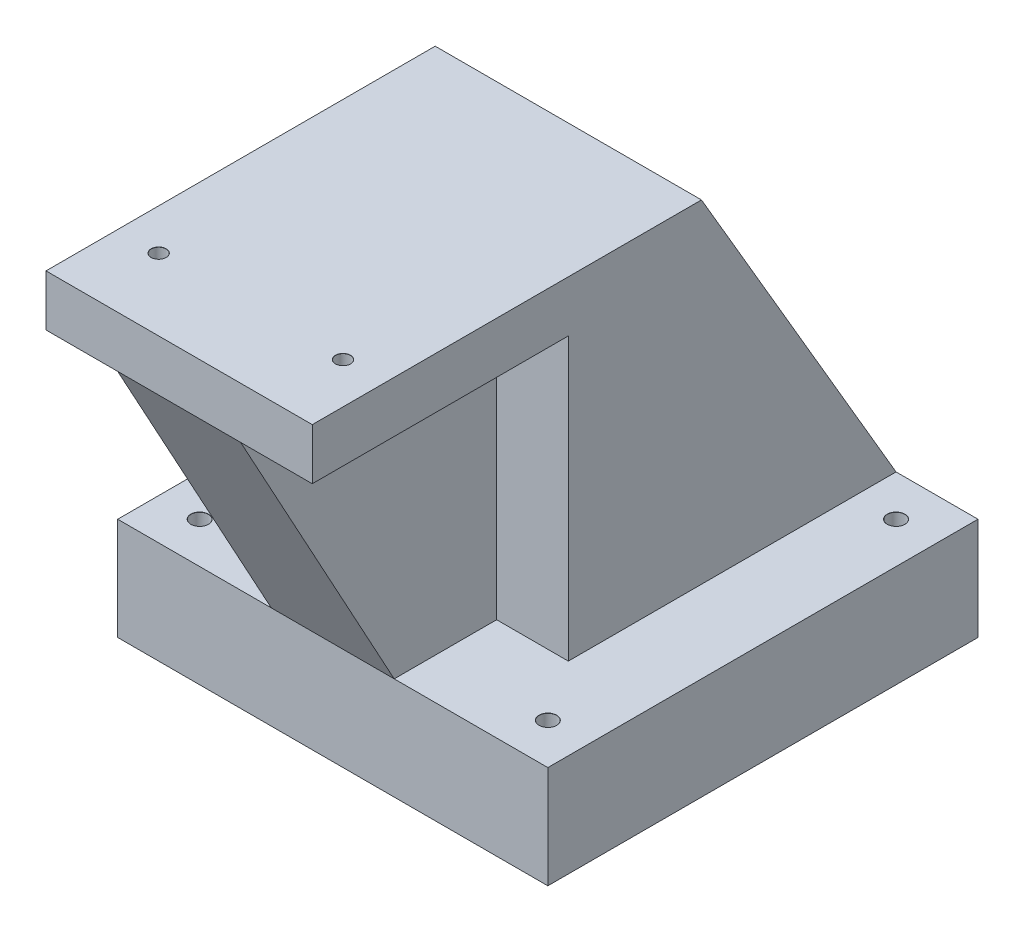
SolidWorks part; units mm, degrees
ref_plane "Front Plane" through (0, 0, 0) normal (0, 0, 1) x (1, 0, 0)
ref_plane "Top Plane" through (0, 0, 0) normal (0, 1, 0) x (1, 0, 0)
ref_plane "Right Plane" through (0, 0, 0) normal (1, 0, 0) x (0, 0, -1)
sketch "Sketch1" plane through (0, 0, 0) normal (0, 1, 0) x (1, 0, 0)
  line L1 (-42, 42) -> (42, 42)
  line L2 (-42, 42) -> (-42, -42)
  line L3 (-42, -42) -> (42, -42)
  line L4 (42, 42) -> (42, -42)
  line L5 (-42, 42) -> (42, -42) construction
  line L6 (-42, -42) -> (42, 42) construction
  point P0 (0, 0)
  dimension "D1" = 84
  dimension "D2" = 84
extrude "Boss-Extrude1" add sketch "Sketch1" along normal blind 20
sketch "Sketch2" plane through (0, 20, 0) normal (0, 1, 0) x (1, 0, 0)
  line L0 (-42, 42) -> (-34, 42) construction
  line L1 (42, 42) -> (-42, 42) construction
  line L2 (-34, 42) -> (-34, 34) construction
  line L3 (42, 34) -> (34, 34) construction
  line L4 (34, -42) -> (34, -34) construction
  line L5 (-42, -34) -> (-34, -34) construction
  point P15 (0, 0)
  dimension "D1" = 8
  dimension "D2" = 8
  dimension "D3" = 4
hole_wizard "M3 Clearance Hole1" positions "Sketch3" profile "Sketch4" hole size "M3" standard "ISO" end condition through all
sketch "Sketch3" plane through (0, 20, 0) normal (0, 1, 0) x (1, 0, 0)
  point P0 (-34, 34)
  point P3 (34, 34)
  point P6 (34, -34)
  point P9 (-34, -34)
sketch "Sketch4" plane through (-34, 20, -34) normal (1, 0, 0) x (0, 0, 1)
  line L0 (0, 0) -> (0, 20)
  line L1 (0, 20) -> (1.7, 20)
  line L2 (1.7, 20) -> (1.7, 0.025)
  line L3 (1.7, 0.025) -> (1.725, 0)
  line L5 (1.725, 0) -> (0, 0)
  line L6 (-1.7, 0.025) -> (-1.725, 0) construction
  line L11 (0, -6.35) -> (0, 107.95) construction
  dimension "Thru Hole Dia." = 3.4
  dimension "Thru Hole Depth" = 20
  dimension "Near C'Sink Dia." = 3.45
  dimension "Near C'Sink Angle" = 90
sketch "Sketch5" plane through (0, 20, 0) normal (0, 1, 0) x (1, 0, 0)
  line L0 (42, -42) -> (42, 42) construction
  line L1 (-42, 4) -> (-26, 4)
  line L2 (-42, 4) -> (-42, -72)
  line L3 (-42, -72) -> (42, -72)
  line L4 (42, 4) -> (42, -72)
  line L5 (-42, 4) -> (42, -72) construction
  line L6 (-42, -72) -> (42, 4) construction
  line L8 (42, 42) -> (-42, 42) construction
  line L9 (-42, 42) -> (-42, -42) construction
  line L11 (-26, 4) -> (-26, 42)
  line L12 (-26, 42) -> (26, 42)
  line L13 (26, 4) -> (26, 42)
  line L14 (26, 4) -> (42, 4)
  line L16 (-42, -42) -> (42, -42) construction
  point P0 (0, 0)
  dimension "D1" = 38
  dimension "D2" = 16
  dimension "D3" = 16
  dimension "D4" = 30
extrude "Boss-Extrude2" add sketch "Sketch5" along normal blind 65
sketch "Sketch7" plane through (0, 85, 0) normal (0, 1, 0) x (1, 0, 0)
  line L0 (0, 42) -> (0, -42) construction
  line L5 (-42, -42) -> (42, -42) construction
  line L6 (42, 4) -> (42, 42) construction
  line L8 (-42, -42) -> (42, -42)
  line L9 (-42, -42) -> (-42, 3)
  line L10 (-42, 3) -> (42, 3)
  line L11 (42, -42) -> (42, 3)
  line L12 (-42, -42) -> (42, 3) construction
  line L13 (-42, 3) -> (42, -42) construction
  line L23 (-37.8179, 3) -> (37.8179, 3)
  line L24 (0, 42) -> (0, 3)
  line L31 (42, -72) -> (42, 4) construction
  point P0 (0, -19.5)
  dimension "D6" = 45
extrude "Boss-Extrude3" add sketch "Sketch7" against normal blind 10
sketch "Sketch10" plane through (0, 85, 0) normal (0, 1, 0) x (1, 0, 0)
  line L0 (-42, -58) -> (42, -58) construction
  line L8 (0, -72) -> (0, 96.5127) construction
  line L9 (-42, -72) -> (42, -72) construction
  point P17 (-18, -58)
  point P21 (0, -58)
  point P26 (18, -58)
  dimension "D1" = 14
  dimension "D5" = 18
hole_wizard "M2.5 Clearance Hole2" positions "Sketch13" profile "Sketch14" hole size "M2.5" standard "ISO"
sketch "Sketch13" plane through (0, 85, 0) normal (0, 1, 0) x (1, 0, 0)
  point P6 (-18, -58)
  point P9 (18, -58)
sketch "Sketch14" plane through (-18, 85, 58) normal (1, 0, 0) x (0, 0, 1)
  line L0 (0, 0) -> (0, 10.8712)
  line L1 (0, 10.8712) -> (1.45, 10)
  line L2 (1.45, 10) -> (1.45, 0.025)
  line L3 (1.45, 0.025) -> (1.475, 0)
  line L5 (1.475, 0) -> (0, 0)
  line L6 (-1.45, 0.025) -> (-1.475, 0) construction
  line L10 (0, 10.8712) -> (-1.45, 10) construction
  line L11 (0, -6.35) -> (0, 107.95) construction
  dimension "Hole Dia." = 2.9
  dimension "Hole Depth" = 10
  dimension "Near C'Sink Dia." = 2.95
  dimension "Near C'Sink Angle" = 90
  dimension "Drill Angle" = 118
sketch "Sketch16" plane through (0, 0, 72) normal (0, 0, 1) x (1, 0, 0)
  line L1 (42, 20) -> (12, 20)
  line L2 (42, 20) -> (42, 75)
  line L3 (42, 75) -> (12, 75)
  line L4 (12, 20) -> (12, 75)
  line L5 (0, 20) -> (0, 137.2972) construction
  line L7 (-42, 20) -> (42, 20) construction
  line L9 (-42, 20) -> (-12, 20)
  line L10 (-42, 20) -> (-42, 75)
  line L11 (-42, 75) -> (-12, 75)
  line L12 (-12, 20) -> (-12, 75)
  line L13 (-42, 85) -> (42, 85) construction
  dimension "D1" = 30
  dimension "D2" = 30
  dimension "D3" = 10
  dimension "D4" = 10
extrude "Cut-Extrude2" cut sketch "Sketch16" against normal blind 50
sketch "Sketch17" plane through (12, 0, 0) normal (1, 0, 0) x (0, 0, -1)
  line L0 (-42, 20) -> (-72, 75)
  line L1 (-72, 75) -> (-72, 20)
  line L2 (-72, 20) -> (-42, 20)
extrude "Cut-Extrude3" cut sketch "Sketch17" against normal through all
sketch "Sketch18" plane through (26, 0, 0) normal (1, 0, 0) x (0, 0, -1)
  line L0 (4, 85) -> (42, 20)
  line L1 (42, 20) -> (42, 85)
  line L2 (42, 85) -> (4, 85)
extrude "Cut-Extrude4" cut sketch "Sketch18" against normal blind 230
sketch "Sketch19" plane through (0, 0, -4) normal (0, 0, -1) x (-1, 0, 0)
  line L0 (42, 85) -> (-42, 85) construction
  line L1 (-26, 20) -> (-42, 20)
  line L2 (-26, 20) -> (-26, 85)
  line L3 (-26, 85) -> (-42, 85)
  line L4 (-42, 20) -> (-42, 85)
  line L5 (-42, 85) -> (-42, 20) construction
  line L6 (42, 85) -> (42, 20) construction
  line L7 (26, 20) -> (42, 20)
  line L8 (26, 20) -> (26, 85)
  line L9 (26, 85) -> (42, 85)
  line L10 (42, 20) -> (42, 85)
extrude "Cut-Extrude5" cut sketch "Sketch19" against normal blind 230
ref_plane "Plane1" through (0, 0, -42) normal (0, 0, -1) x (-1, 0, 0)
